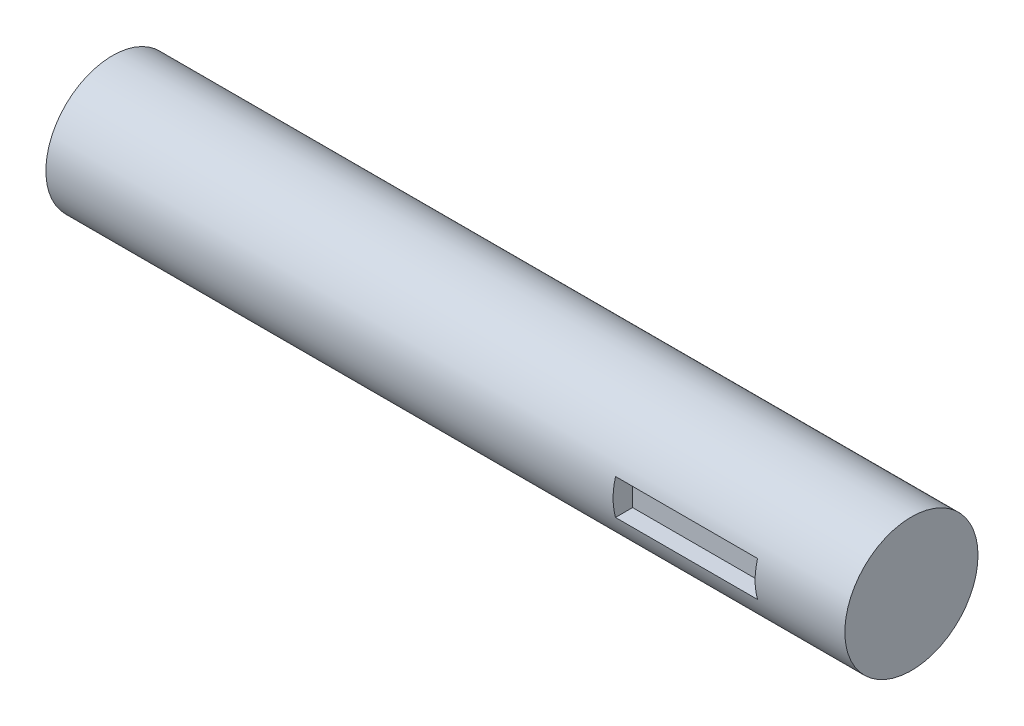
SolidWorks part; units mm, degrees
ref_plane "Front Plane" through (0, 0, 0) normal (0, 0, 1) x (1, 0, 0)
ref_plane "Top Plane" through (0, 0, 0) normal (0, 1, 0) x (1, 0, 0)
ref_plane "Right Plane" through (0, 0, 0) normal (1, 0, 0) x (0, 0, -1)
sketch "Sketch2" plane through (0, 0, 0) normal (0, 0, 1) x (1, 0, 0)
  line L0 (0, 0) -> (-113.9604, 0) construction
  line L1 (0, 0) -> (180, 0)
  line L2 (0, 0) -> (0, 15)
  line L3 (0, 15) -> (180, 15)
  line L4 (180, 0) -> (180, 15)
  dimension "D1" = 30
  dimension "D2" = 180
revolve "Revolve1" add sketch "Sketch2" angle 360 about L0
ref_plane "Plane1" through (0, 0, 15) normal (0, 0, 1) x (1, 0, 0)
sketch "Sketch3" plane through (0, 0, 15) normal (0, 0, 1) x (1, 0, 0)
  line L0 (159.7864, -4) -> (159.7864, 4)
  line L2 (150.8605, 0) -> (66.8605, 0) construction
  line L3 (159.7864, 4) -> (127.7864, 4)
  line L4 (127.7864, 4) -> (127.7864, -4)
  line L5 (159.7864, -4) -> (127.7864, -4)
  point P8 (127.7864, 0)
  point P9 (159.7864, 0)
extrude "Cut-Extrude1" cut sketch "Sketch3" against normal blind 4.4
